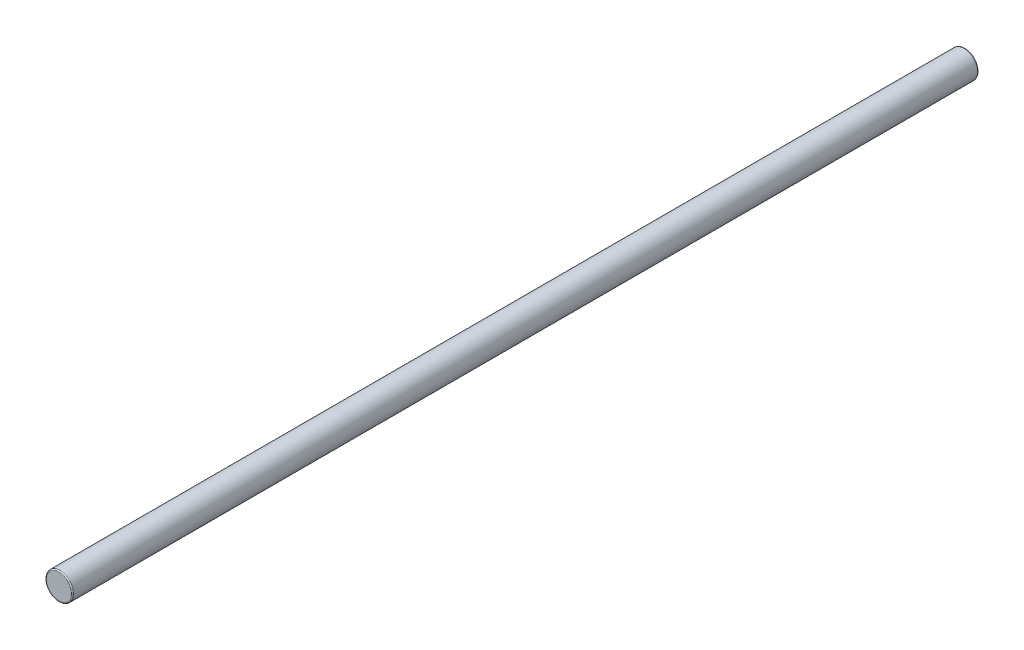
SolidWorks part; units mm, degrees
material "AISI 1020"
ref_plane "Alzado" through (0, 0, 0) normal (0, 0, 1) x (1, 0, 0)
ref_plane "Planta" through (0, 0, 0) normal (0, 1, 0) x (1, 0, 0)
ref_plane "Vista lateral" through (0, 0, 0) normal (1, 0, 0) x (0, 0, -1)
sketch "Croquis1" plane through (0, 0, 0) normal (0, 0, 1) x (1, 0, 0)
  circle A0 centre (0, 0) radius 6
  dimension "D1" = 12
extrude "Saliente-Extruir1" add sketch "Croquis1" along normal blind 400
fillet "Redondeo1" radius 0.5 2 edges at (6, 0, 0) (6, 0, 400)
